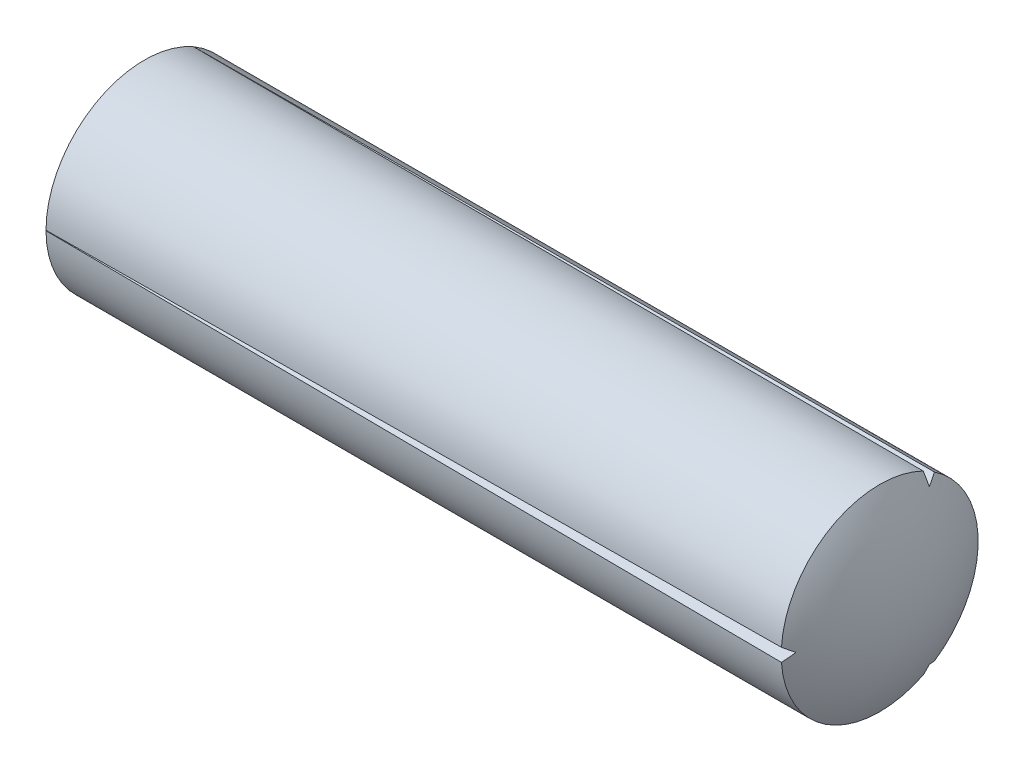
SolidWorks part; units mm, degrees
ref_plane "Plane1" through (0, 0, 0) normal (0, 0, 1) x (1, 0, 0)
ref_plane "Plane2" through (0, 0, 0) normal (0, 1, 0) x (1, 0, 0)
ref_plane "Plane3" through (0, 0, 0) normal (1, 0, 0) x (0, 0, -1)
sketch "Sketch1" plane through (0, 0, 0) normal (0, 0, 1) x (1, 0, 0)
  line L0 (-40, 0) -> (40, 0) construction
  line L1 (-100, 0) -> (-100, 1.25)
  line L2 (-96.6819, 12.5) -> (-3.3494, 12.5)
  line L4 (0, 0) -> (-100, 0)
  arc A0 (-96.6819, 12.5) -> (-100, 1.25) centre (-75.0313, 0) ccw
  arc A1 (0, 0) -> (-3.3494, 12.5) centre (-25, 0) ccw
  dimension "D1" = 25
  dimension "D2" = 25
  dimension "Diameter" = 25
  dimension "Length" = 100
  dimension "D3" = 2.5
revolve "Base-Revolve" add sketch "Sketch1" angle 360 about L0
sketch "Sketch2" plane through (0, 0, 0) normal (1, 0, 0) x (0, 0, -1)
  line L0 (0, 0) -> (-15, 0) construction
  line L1 (-11.25, 0) -> (-12.5, 0.8753)
  line L2 (-11.25, 0) -> (-12.5, -0.8753)
  line L3 (-12.5, -0.8753) -> (-12.5, 0.8753)
  circle A0 centre (0, 0) radius 11.25 construction
  circle A1 centre (0, 0) radius 12.5 construction
  dimension "D1" = 22.5
  dimension "D2" = 70
  dimension "D3" = 35
sketch "Sketch4" plane through (0, 0, 0) normal (0, 1, 0) x (1, 0, 0)
  line L0 (-110, 0) -> (10, 0) construction
  line L1 (-40, 0) -> (40, 0) construction
  line L2 (0, -11.25) -> (-100, -12.5)
  dimension "D1" = 22.5
  dimension "D2" = 100
  dimension "D3" = 25
sweep "Cut-Sweep1" cut profiles "Sketch2" path "Sketch4"
pattern_circular "CirPattern1" count 3 over 360 about axis through (0, 0, 0) along (1, 0, 0) of "Cut-Sweep1"
equation "\"D1@Sketch1\" = \"Diameter@Sketch1\""
equation "\"D2@Sketch1\" = \"Diameter@Sketch1\""
equation "\"D3@Sketch1\" = \"Diameter@Sketch1\" * .1"
equation "\"D1@Sketch2\" = \"Diameter@Sketch1\" * .9"
equation "\"D3@Sketch2\" = \"D2@Sketch2\" / 2"
equation "\"D1@Sketch4\" = \"D1@Sketch2\""
equation "\"D2@Sketch4\" = \"Length@Sketch1\""
equation "\"D3@Sketch4\" = \"Diameter@Sketch1\""
